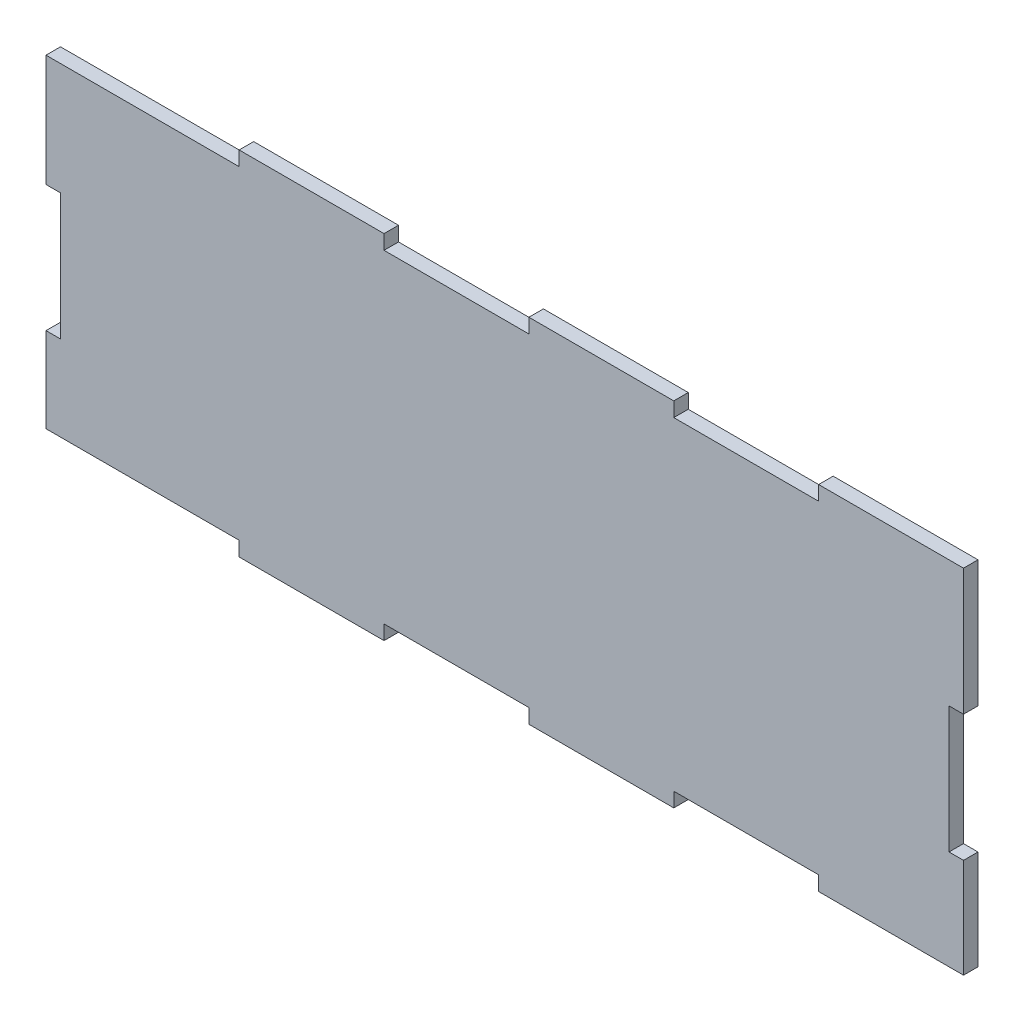
SolidWorks part; units mm, degrees
material "Acrylic (Medium-high impact)"
ref_plane "Front Plane" through (0, 0, 0) normal (0, 0, 1) x (1, 0, 0)
ref_plane "Top Plane" through (0, 0, 0) normal (0, 1, 0) x (1, 0, 0)
ref_plane "Right Plane" through (0, 0, 0) normal (1, 0, 0) x (0, 0, -1)
sketch "Sketch1" plane through (0, 0, 0) normal (0, 0, 1) x (1, 0, 0)
  line L252 (0, 70) -> (0, 73)
  line L253 (0, 70) -> (-10, 70)
  line L254 (60, 73) -> (90, 73)
  line L255 (0, 0) -> (180, 0)
  line L256 (0, 0) -> (0, 3)
  line L257 (0, 73) -> (180, 73)
  line L258 (180, 0) -> (180, 73)
  line L259 (0, 73) -> (30, 73)
  line L260 (0, 73) -> (0, 70)
  line L261 (0, 70) -> (30, 70)
  line L262 (30, 73) -> (30, 70)
  line L263 (60, 73) -> (60, 70)
  line L264 (60, 70) -> (90, 70)
  line L265 (90, 73) -> (90, 70)
  line L266 (120, 73) -> (150, 73)
  line L267 (120, 73) -> (120, 70)
  line L268 (120, 70) -> (150, 70)
  line L269 (150, 73) -> (150, 70)
  line L270 (60, 3) -> (90, 3)
  line L271 (60, 3) -> (60, 0)
  line L272 (60, 0) -> (90, 0)
  line L273 (90, 3) -> (90, 0)
  line L274 (120, 3) -> (150, 3)
  line L275 (120, 3) -> (120, 0)
  line L276 (120, 0) -> (150, 0)
  line L277 (150, 3) -> (150, 0)
  line L278 (0, 3) -> (30, 3)
  line L279 (0, 3) -> (0, 0)
  line L280 (0, 0) -> (30, 0)
  line L281 (30, 3) -> (30, 0)
  line L282 (177, 46.8) -> (177, 20.6)
  line L287 (177, 46.8) -> (180, 46.8)
  line L288 (180, 46.8) -> (180, 20.6)
  line L289 (177, 20.6) -> (180, 20.6)
  line L290 (-10, 70) -> (-10, 3)
  line L291 (-10, 3) -> (0, 3)
  line L293 (-10, 46.8) -> (-7, 46.8)
  line L294 (-10, 46.8) -> (-10, 20.6)
  line L295 (-10, 20.6) -> (-7, 20.6)
  line L296 (-7, 46.8) -> (-7, 20.6)
  dimension "D1" = 180
  dimension "D2" = 73
  dimension "D3" = 3
  dimension "D4" = 30
  dimension "D7" = 3
  dimension "D8" = 3
  dimension "D5" = 23.2
  dimension "D6" = 26.2
  dimension "D12" = 10
  dimension "D10" = 3
  dimension "D11" = 26.2
  dimension "D9" = 2
extrude "Boss-Extrude1" add sketch "Sketch1" along normal blind 3
